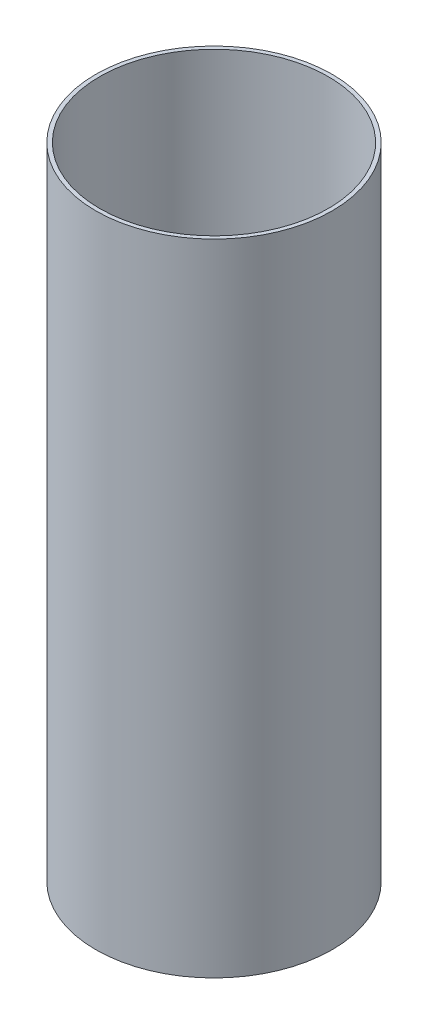
SolidWorks part; units mm, degrees
ref_plane "前视基准面" through (0, 0, 0) normal (0, 0, 1) x (1, 0, 0)
ref_plane "上视基准面" through (0, 0, 0) normal (0, 1, 0) x (1, 0, 0)
ref_plane "右视基准面" through (0, 0, 0) normal (1, 0, 0) x (0, 0, -1)
sketch "草图1" plane through (0, 0, 0) normal (0, 1, 0) x (1, 0, 0)
  circle A0 centre (0, 0) radius 4.5
  circle A1 centre (0, 0) radius 9
  dimension "D1" = 9
  dimension "D2" = 18
extrude "凸台-拉伸2" add sketch "草图1" against normal blind 2
sketch "草图2" plane through (0, 0, 0) normal (0, 1, 0) x (1, 0, 0)
  circle A0 centre (0, 0) radius 8.7
  circle A1 centre (0, 0) radius 9 construction
  circle A2 centre (0, 0) radius 9
  dimension "D1" = 17.4
extrude "凸台-拉伸3" add sketch "草图2" along normal blind 46.7
